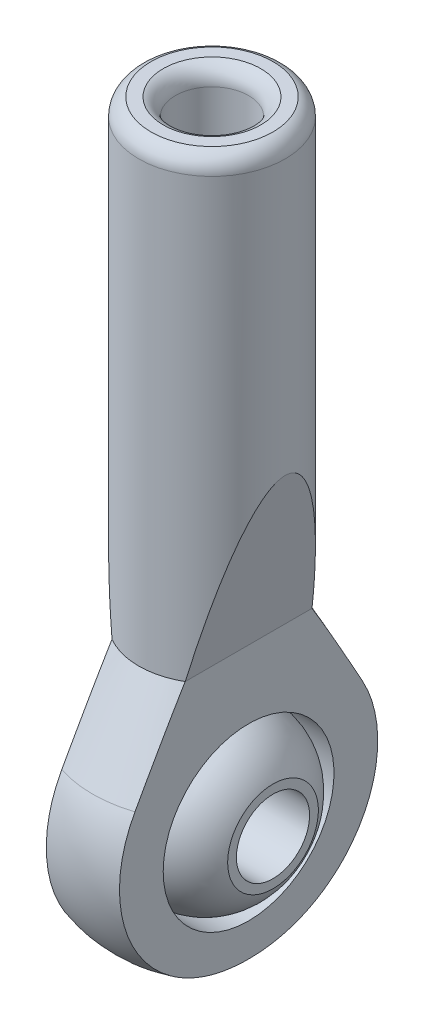
SolidWorks part; units mm, degrees
material "普通碳钢"
ref_plane "前视" through (0, 0, 0) normal (0, 0, 1) x (1, 0, 0)
ref_plane "上视" through (0, 0, 0) normal (0, 1, 0) x (1, 0, 0)
ref_plane "右视" through (0, 0, 0) normal (1, 0, 0) x (0, 0, -1)
sketch "草图1" plane through (0, 0, 0) normal (1, 0, 0) x (0, 0, -1)
  line L0 (0, 0) -> (0, -10.7071) construction
  line L1 (0, 0) -> (2.25, 0) construction
  line L2 (1.5, -0.7071) -> (1.5, -10.7071)
  line L3 (0, -10.7071) -> (0, -30)
  line L4 (3, -18.7071) -> (3, -0.7071)
  line L5 (2.5, 0) -> (2, 0)
  line L6 (2.25, 0) -> (2.25, -0.7071) construction
  line L7 (0, -10.7071) -> (1.5, -10.7071)
  line L8 (3, -18.7071) -> (4.8944, -22.3032)
  line L9 (0.2462, -24.7519) -> (5.5, -24.7519) construction
  arc A0 (1.5, -0.7071) -> (2, 0) centre (2.25, -0.7071) cw
  arc A1 (2.5, 0) -> (3, -0.7071) centre (2.25, -0.7071) cw
  arc A4 (0, -30) -> (4.8944, -22.3032) centre (0.2462, -24.7519) ccw
  dimension "D1" = 3
  dimension "D3" = 30
  dimension "D2" = 6
  dimension "D4" = 0.5
  dimension "D5" = 10
  dimension "D6" = 18
  dimension "D7" = 11
revolve "旋转1" add sketch "草图1" angle 360 about L0
sketch "草图5" plane through (0, 0, 0) normal (0, 0, 1) x (1, 0, 0)
  line L0 (-3, -11.9401) -> (-1.5, -18.7071)
  line L1 (-3, -0.7071) -> (-3, -18.7071) construction
  line L2 (3, -18.7071) -> (-3, -18.7071) construction
  line L3 (0, 0) -> (0, -30) construction
  line L4 (3, -11.9401) -> (1.5, -18.7071)
  line L5 (-1.5, -18.7071) -> (-1.5, -33.6879)
  line L6 (-1.5, -33.6879) -> (-8.7269, -33.6879)
  line L7 (-8.7269, -33.6879) -> (-8.7269, -11.9401)
  line L8 (-8.7269, -11.9401) -> (-3, -11.9401)
  line L9 (1.5, -33.6879) -> (8.7269, -33.6879)
  line L10 (1.5, -18.7071) -> (1.5, -33.6879)
  line L11 (8.7269, -33.6879) -> (8.7269, -11.9401)
  line L12 (8.7269, -11.9401) -> (3, -11.9401)
  dimension "D1" = 3
extrude "切除-拉伸1" cut sketch "草图5" against normal mid plane 16
sketch "草图6" plane through (-1.5, 0, 0) normal (-1, 0, 0) x (0, 0, 1)
  line L0 (0, -30) -> (0, 0) construction
  circle A0 centre (0, -25) radius 3.5
  dimension "D1" = 25
  dimension "D2" = 7
extrude "切除-拉伸2" cut sketch "草图6" against normal blind 16
sketch "草图7" plane through (0, 0, 0) normal (0, 0, 1) x (1, 0, 0)
  line L0 (1.5, -21.5) -> (1.5, -28.5) construction
  line L1 (-1.5, -25) -> (4.9244, -25) construction
  line L2 (-1.5, -22.3032) -> (-1.5, -29.854) construction
  line L6 (0, 0) -> (0, -25) construction
  line L10 (-2.5, -26.5) -> (2.5, -26.5)
  line L11 (2.5, -26.5) -> (2.5, -26.8585)
  line L12 (-2.5, -26.5) -> (-2.5, -26.8585)
  arc A2 (2.5, -26.8585) -> (-2.5, -26.8585) centre (0, -25.6607) cw
  dimension "D1" = 5
  dimension "D2" = 3
  dimension "D3" = 3.5
revolve "旋转3" add sketch "草图7" angle 360 about L1
